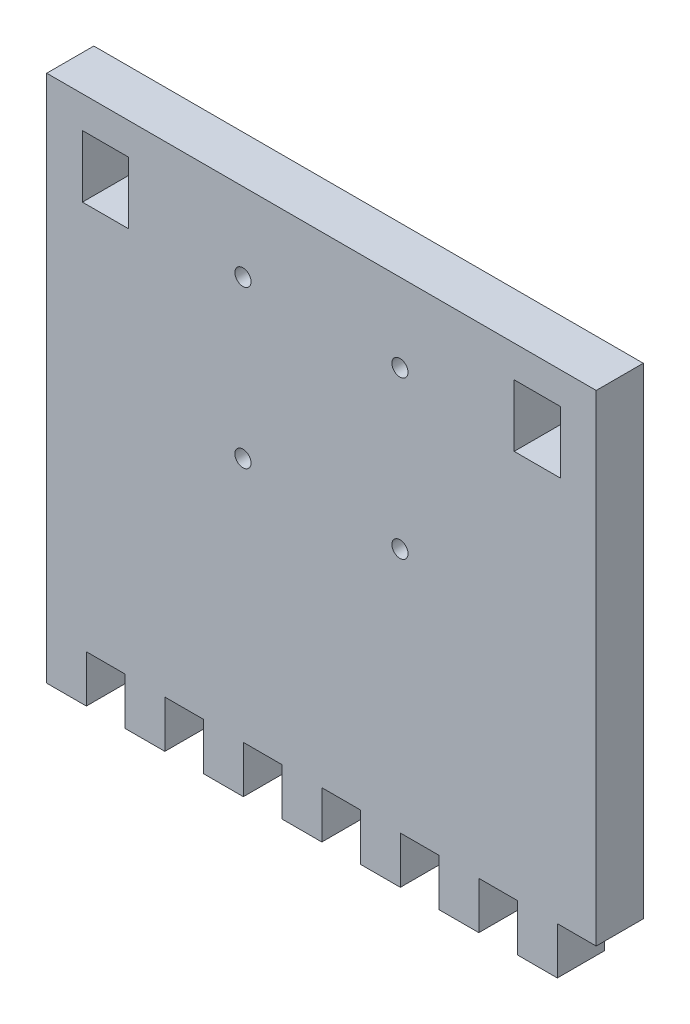
SolidWorks part; units mm, degrees
ref_plane "Plan de face" through (0, 0, 0) normal (0, 0, 1) x (1, 0, 0)
ref_plane "Plan de dessus" through (0, 0, 0) normal (0, 1, 0) x (1, 0, 0)
ref_plane "Plan de droite" through (0, 0, 0) normal (1, 0, 0) x (0, 0, -1)
sketch "Esquisse1" plane through (0, 0, 0) normal (0, 0, 1) x (1, 0, 0)
  line L0 (0, 0) -> (0, 67.3)
  line L1 (0, 67.3) -> (70, 67.3)
  line L2 (70, 67.3) -> (70, 6)
  line L3 (70, 6) -> (65.05, 6)
  line L4 (65.05, 6) -> (65.05, 0)
  line L5 (65.05, 0) -> (60, 0)
  line L6 (60, 0) -> (60, 6)
  line L7 (60, 6) -> (55.05, 6)
  line L8 (55.05, 6) -> (55.05, 0)
  line L10 (30, 0) -> (30, 6)
  line L11 (30, 6) -> (25.05, 6)
  line L12 (25.05, 6) -> (25.05, 0)
  line L13 (25.05, 0) -> (20, 0)
  line L14 (20, 0) -> (20, 6)
  line L15 (20, 6) -> (15.05, 6)
  line L16 (15.05, 6) -> (15.05, 0)
  line L17 (15.05, 0) -> (10, 0)
  line L18 (10, 0) -> (10, 6)
  line L19 (10, 6) -> (5.05, 6)
  line L20 (5.05, 6) -> (5.05, 0)
  line L21 (5.05, 0) -> (0, 0)
  line L22 (30, 0) -> (35.05, 0)
  line L23 (35.05, 0) -> (35.05, 6)
  line L24 (35.05, 6) -> (40, 6)
  line L25 (40, 6) -> (40, 0)
  line L26 (40, 0) -> (45.05, 0)
  line L27 (45.05, 0) -> (45.05, 6)
  line L28 (45.05, 6) -> (50, 6)
  line L29 (50, 6) -> (50, 0)
  line L30 (50, 0) -> (55.05, 0)
  line L31 (4.55, 59.3) -> (65.45, 59.3) construction
  line L32 (4.55, 63.25) -> (10.45, 63.25)
  line L33 (4.55, 63.25) -> (4.55, 55.35)
  line L34 (4.55, 55.35) -> (10.45, 55.35)
  line L35 (10.45, 63.25) -> (10.45, 55.35)
  line L36 (59.55, 63.25) -> (65.45, 63.25)
  line L37 (59.55, 63.25) -> (59.55, 55.35)
  line L38 (59.55, 55.35) -> (65.45, 55.35)
  line L39 (65.45, 63.25) -> (65.45, 55.35)
  line L40 (25, 57.3) -> (25, 37.3) construction
  line L41 (25, 37.3) -> (45, 37.3) construction
  line L42 (45, 37.3) -> (45, 57.3) construction
  line L43 (45, 57.3) -> (25, 57.3) construction
  line L44 (35, 57.3) -> (35, 37.3) construction
  line L45 (25, 47.3) -> (45, 47.3) construction
  line L46 (62.5, 63.25) -> (62.5, 55.35) construction
  line L47 (62.5, 55.35) -> (59.55, 55.35) construction
  line L48 (7.5, 55.35) -> (7.5, 63.25) construction
  line L49 (10.45, 55.35) -> (7.5, 55.35) construction
  circle A0 centre (25, 57.3) radius 1.03
  circle A1 centre (45, 57.3) radius 1.03
  circle A2 centre (25, 37.3) radius 1.03
  circle A3 centre (45, 37.3) radius 1.03
  point P54 (35, 47.3)
  dimension "D15" = 2.06
  dimension "D16" = 41.3
  dimension "D1" = 70
  dimension "D2" = 5.05
  dimension "D3" = 4.95
  dimension "D4" = 6
  dimension "D5" = 8
  dimension "D6" = 5.9
  dimension "D7" = 5.9
  dimension "D8" = 7.5
  dimension "D9" = 7.5
  dimension "D10" = 7.9
  dimension "D11" = 7.9
  dimension "D12" = 20
  dimension "D13" = 20
  dimension "D14" = 20
extrude "Boss.-Extru.1" add sketch "Esquisse1" along normal blind 6
